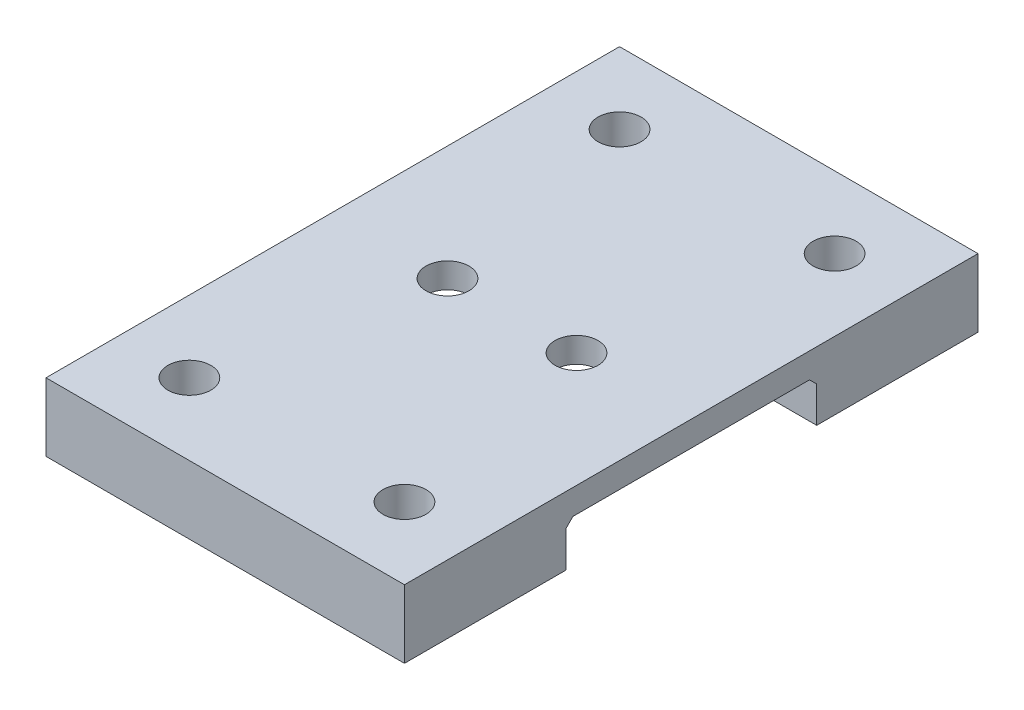
SolidWorks part; units mm, degrees
ref_plane "Front" through (0, 0, 0) normal (0, 0, 1) x (1, 0, 0)
ref_plane "Top" through (0, 0, 0) normal (0, 1, 0) x (1, 0, 0)
ref_plane "Right" through (0, 0, 0) normal (1, 0, 0) x (0, 0, -1)
sketch "Sketch1" plane through (0, 0, 0) normal (0, 1, 0) x (1, 0, 0)
  line L0 (0, 50.2692) -> (0, 0) construction
  line L1 (-25, -40) -> (25, -40)
  line L2 (-25, -40) -> (-25, 40)
  line L3 (-25, 40) -> (25, 40)
  line L4 (25, -40) -> (25, 40)
  line L5 (-25, -40) -> (25, 40) construction
  line L6 (-25, 40) -> (25, -40) construction
  line L7 (0, 0) -> (-48.8151, 0) construction
  circle A0 centre (-15, 30) radius 3
  circle A1 centre (15, 30) radius 3
  circle A2 centre (-15, -30) radius 3
  circle A3 centre (15, -30) radius 3
  point P0 (0, 0)
  dimension "D1" = 10
  dimension "D2" = 10
extrude "Boss-Extrude1" add sketch "Sketch1" along normal blind 9.5
sketch "Sketch2" plane through (0, 0, 0) normal (0, -1, 0) x (1, 0, 0)
  line L6 (-40.0505, -17.5) -> (40.0505, -17.5)
  line L10 (-40.0505, -17.5) -> (-40.0505, 17.5)
  line L11 (-40.0505, 17.5) -> (40.0505, 17.5)
  line L12 (40.0505, -17.5) -> (40.0505, 17.5)
  line L13 (-40.0505, -17.5) -> (40.0505, 17.5) construction
  line L14 (-40.0505, 17.5) -> (40.0505, -17.5) construction
  point P0 (0, 0)
  point P2 (0, 0)
extrude "Cut-Extrude1" cut sketch "Sketch2" against normal blind 6
sketch "Sketch3" plane through (0, 6, 0) normal (0, -1, 0) x (1, 0, 0)
  circle A0 centre (0, 0) radius 16 construction
  circle A1 centre (-9, 0) radius 3
  circle A2 centre (9, 0) radius 3
  point P11 (0, 0)
  dimension "D1" = 9
  dimension "D2" = 2
extrude "Cut-Extrude2" cut sketch "Sketch3" against normal through all
chamfer "Chamfer1" distance 1 angle 45 2 edges at (0, 6, -17.5) (0, 6, 17.5)
